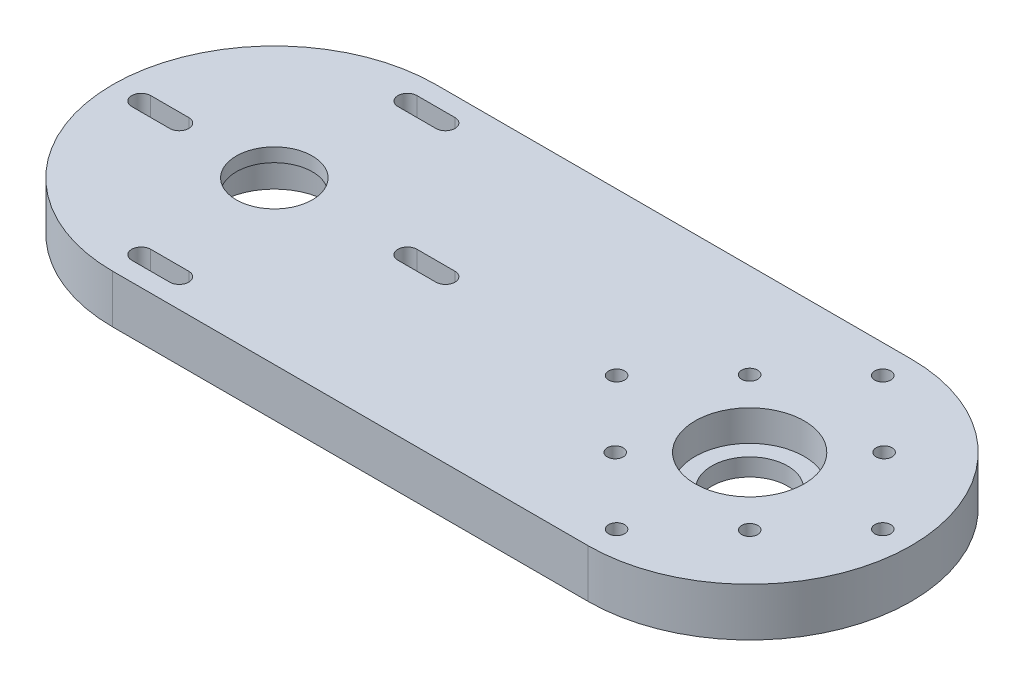
SolidWorks part; units mm, degrees
ref_plane "Front Plane" through (0, 0, 0) normal (0, 0, 1) x (1, 0, 0)
ref_plane "Top Plane" through (0, 0, 0) normal (0, 1, 0) x (1, 0, 0)
ref_plane "Right Plane" through (0, 0, 0) normal (1, 0, 0) x (0, 0, -1)
sketch "Sketch1" plane through (0, 0, 0) normal (0, 1, 0) x (1, 0, 0)
  line L0 (-125, 0) -> (0, 0) construction
  line L1 (-125, 42.5) -> (0, 42.5)
  line L6 (-125, -42.5) -> (0, -42.5)
  line L7 (-125, 35) -> (-115, 35) construction
  line L8 (-125, 37.5) -> (-115, 37.5)
  line L9 (-125, 32.5) -> (-115, 32.5)
  line L10 (-160, 0) -> (-150, 0) construction
  line L11 (-160, 2.5) -> (-150, 2.5)
  line L12 (-160, -2.5) -> (-150, -2.5)
  line L13 (-90, 0) -> (-80, 0) construction
  line L14 (-90, 2.5) -> (-80, 2.5)
  line L15 (-90, -2.5) -> (-80, -2.5)
  line L16 (-125, -35) -> (-115, -35) construction
  line L17 (-125, -32.5) -> (-115, -32.5)
  line L18 (-125, -37.5) -> (-115, -37.5)
  line L19 (17.6777, -17.6777) -> (-17.6777, 17.6777) construction
  line L21 (-17.6777, -17.6777) -> (17.6777, 17.6777) construction
  circle A1 centre (-125, 0) radius 10
  circle A4 centre (-125, 0) radius 14.2875 construction
  circle A5 centre (0, 0) radius 10
  circle A8 centre (-125, 0) radius 35 construction
  circle A13 centre (-125, 0) radius 42.5
  circle A14 centre (0, 0) radius 42.5
  circle A15 centre (0, 0) radius 35 construction
  circle A16 centre (0, 35) radius 2.1
  circle A17 centre (35, 0) radius 2.1
  circle A18 centre (0, -35) radius 2.1
  circle A19 centre (-35, 0) radius 2.1
  arc A20 (-125, 37.5) -> (-125, 32.5) centre (-125, 35) ccw
  arc A21 (-115, 32.5) -> (-115, 37.5) centre (-115, 35) ccw
  arc A22 (-160, 2.5) -> (-160, -2.5) centre (-160, 0) ccw
  arc A23 (-150, -2.5) -> (-150, 2.5) centre (-150, 0) ccw
  arc A24 (-90, 2.5) -> (-90, -2.5) centre (-90, 0) ccw
  arc A25 (-80, -2.5) -> (-80, 2.5) centre (-80, 0) ccw
  arc A26 (-125, -32.5) -> (-125, -37.5) centre (-125, -35) ccw
  arc A27 (-115, -37.5) -> (-115, -32.5) centre (-115, -35) ccw
  circle A28 centre (-125, 0) radius 27.94 construction
  circle A29 centre (0, 0) radius 25 construction
  circle A30 centre (-17.6777, 17.6777) radius 2.1
  circle A31 centre (17.6777, -17.6777) radius 2.1
  circle A32 centre (-17.6777, -17.6777) radius 2.1
  circle A33 centre (17.6777, 17.6777) radius 2.1
  point P17 (-120, 35)
  point P22 (-155, 0)
  point P37 (-85, 0)
  point P44 (-120, -35)
  dimension "D2" = 20
  dimension "D4" = 4.2
  dimension "D5" = 45
  dimension "D6" = 28.575
  dimension "D7" = 20
  dimension "D9" = 55.88
  dimension "D10" = 85
  dimension "D8" = 70
  dimension "D11" = 10
  dimension "D12" = 70
  dimension "D13" = 5
  dimension "D14" = 50
  dimension "D15" = 4.2
  dimension "D3" = 125
extrude "Boss-Extrude1" add sketch "Sketch1" against normal blind 12.7
sketch "Sketch2" plane through (0, 0, 0) normal (0, 1, 0) x (1, 0, 0)
  circle A0 centre (-125, 0) radius 14.2875 construction
  circle A1 centre (0, 0) radius 14.35
  dimension "D1" = 28.575
  dimension "D2" = 28.7
extrude "Cut-Extrude1" cut sketch "Sketch2" against normal blind 8.1
sketch "Sketch3" plane through (0, 0, 0) normal (0, 1, 0) x (1, 0, 0)
  circle A0 centre (-125, 0) radius 14.35
  dimension "D1" = 28.7
extrude "Cut-Extrude2" cut sketch "Sketch3" along normal blind 9.1 from surface at -12.7 starting at face at (-62.5, -12.7, 0)
sketch "Sketch4" plane through (0, 0, 0) normal (0, 1, 0) x (1, 0, 0)
  line L0 (-150, 0) -> (-160, 0) construction
  line L1 (-150, -4.05) -> (-160, -4.05)
  line L2 (-150, 4.05) -> (-160, 4.05)
  line L3 (-125, -35) -> (-115, -35) construction
  line L4 (-125, -30.95) -> (-115, -30.95)
  line L5 (-125, -39.05) -> (-115, -39.05)
  line L6 (-80, 0) -> (-90, 0) construction
  line L7 (-80, -4.05) -> (-90, -4.05)
  line L8 (-80, 4.05) -> (-90, 4.05)
  line L9 (-125, 35) -> (-115, 35) construction
  line L10 (-125, 39.05) -> (-115, 39.05)
  line L11 (-125, 30.95) -> (-115, 30.95)
  arc A0 (-150, -4.05) -> (-150, 4.05) centre (-150, 0) ccw
  arc A1 (-160, 4.05) -> (-160, -4.05) centre (-160, 0) ccw
  arc A2 (-125, -30.95) -> (-125, -39.05) centre (-125, -35) ccw
  arc A3 (-115, -39.05) -> (-115, -30.95) centre (-115, -35) ccw
  arc A4 (-80, -4.05) -> (-80, 4.05) centre (-80, 0) ccw
  arc A5 (-90, 4.05) -> (-90, -4.05) centre (-90, 0) ccw
  arc A6 (-125, 39.05) -> (-125, 30.95) centre (-125, 35) ccw
  arc A7 (-115, 30.95) -> (-115, 39.05) centre (-115, 35) ccw
  circle A8 centre (-125, 0) radius 35 construction
  point P3 (-155, 0)
  point P8 (-120, -35)
  point P15 (-85, 0)
  point P22 (-120, 35)
  dimension "D3" = 70
  dimension "D1" = 10
  dimension "D2" = 8.1
extrude "Cut-Extrude3" cut sketch "Sketch4" along normal blind 5 from surface at -12.7 starting at face at (-125, -12.7, 14.35)
